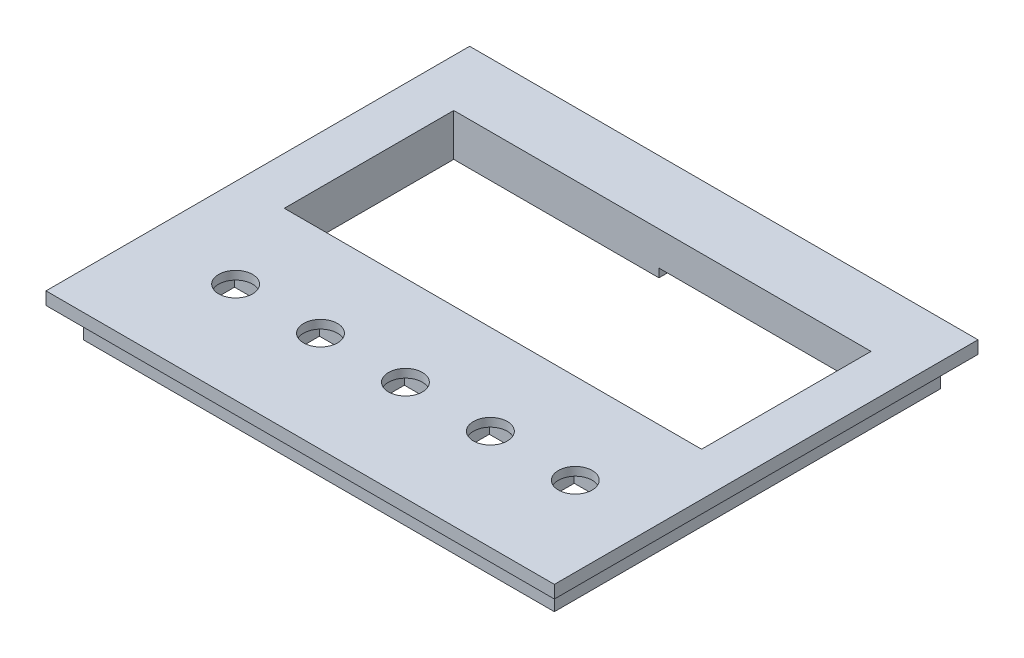
SolidWorks part; units mm, degrees
ref_plane "Front Plane" through (0, 0, 0) normal (0, 0, 1) x (1, 0, 0)
ref_plane "Top Plane" through (0, 0, 0) normal (0, 1, 0) x (1, 0, 0)
ref_plane "Right Plane" through (0, 0, 0) normal (1, 0, 0) x (0, 0, -1)
sketch "Sketch1" plane through (0, 0, 0) normal (0, 1, 0) x (1, 0, 0)
  line L1 (-59.6887, 52.0519) -> (60.3113, 52.0519)
  line L2 (-59.6887, 52.0519) -> (-59.6887, -47.9481)
  line L3 (-59.6887, -47.9481) -> (60.3113, -47.9481)
  line L4 (60.3113, 52.0519) -> (60.3113, -47.9481)
  dimension "D1" = 100
  dimension "D2" = 120
extrude "Boss-Extrude1" add sketch "Sketch1" along normal blind 10
sketch "Sketch2" plane through (0, 10, 0) normal (0, 1, 0) x (1, 0, 0)
  line L0 (60.3113, 52.0519) -> (-59.6887, 52.0519) construction
  line L1 (-48.4387, 37.0519) -> (50.0613, 37.0519)
  line L2 (-48.4387, 37.0519) -> (-48.4387, -2.9481)
  line L3 (-48.4387, -2.9481) -> (50.0613, -2.9481)
  line L4 (50.0613, 37.0519) -> (50.0613, -2.9481)
  line L5 (-59.6887, 52.0519) -> (-59.6887, -47.9481) construction
  dimension "D1" = 98.5
  dimension "D2" = 40
  dimension "D3" = 15
  dimension "D4" = 11.25
extrude "Cut-Extrude1" cut sketch "Sketch2" against normal blind 10
sketch "Sketch3" plane through (0, 0, 0) normal (0, -1, 0) x (1, 0, 0)
  line L0 (-59.6887, 47.9481) -> (60.3113, 47.9481) construction
  line L1 (-55.2887, 43.5481) -> (55.9113, 43.5481)
  line L2 (-55.2887, 43.5481) -> (-55.2887, -47.6519)
  line L3 (-55.2887, -47.6519) -> (55.9113, -47.6519)
  line L4 (55.9113, 43.5481) -> (55.9113, -47.6519)
  line L5 (-59.6887, -52.0519) -> (-59.6887, 47.9481) construction
  line L7 (60.3113, -52.0519) -> (-59.6887, -52.0519)
  line L8 (60.3113, -52.0519) -> (60.3113, 47.9481)
  line L9 (60.3113, 47.9481) -> (-59.6887, 47.9481)
  line L10 (-59.6887, -52.0519) -> (-59.6887, 47.9481)
  dimension "D1" = 4.4
  dimension "D2" = 4.4
  dimension "D3" = 4.4
  dimension "D4" = 4.4
extrude "Cut-Extrude3" cut sketch "Sketch3" against normal blind 7
sketch "Sketch4" plane through (0, 0, 0) normal (0, -1, 0) x (1, 0, 0)
  line L0 (-48.4387, 2.9481) -> (50.0613, 2.9481) construction
  line L1 (-48.1793, 39.9481) -> (-30.1793, 39.9481)
  line L2 (-48.1793, 39.9481) -> (-48.1793, 14.9481)
  line L3 (-48.1793, 14.9481) -> (-30.1793, 14.9481)
  line L4 (-30.1793, 39.9481) -> (-30.1793, 14.9481)
  line L5 (-28.1338, 39.9481) -> (-10.1338, 39.9481)
  line L6 (-28.1338, 39.9481) -> (-28.1338, 14.9481)
  line L7 (-28.1338, 14.9481) -> (-10.1338, 14.9481)
  line L8 (-10.1338, 39.9481) -> (-10.1338, 14.9481)
  line L9 (-8.0883, 39.9481) -> (9.9117, 39.9481)
  line L10 (-8.0883, 39.9481) -> (-8.0883, 14.9481)
  line L11 (-8.0883, 14.9481) -> (9.9117, 14.9481)
  line L12 (9.9117, 39.9481) -> (9.9117, 14.9481)
  line L13 (11.9573, 39.9481) -> (29.9573, 39.9481)
  line L14 (11.9573, 39.9481) -> (11.9573, 14.9481)
  line L15 (11.9573, 14.9481) -> (29.9573, 14.9481)
  line L16 (29.9573, 39.9481) -> (29.9573, 14.9481)
  line L17 (32.0028, 39.9481) -> (50.0028, 39.9481)
  line L18 (32.0028, 39.9481) -> (32.0028, 14.9481)
  line L19 (32.0028, 14.9481) -> (50.0028, 14.9481)
  line L20 (50.0028, 39.9481) -> (50.0028, 14.9481)
  line L21 (-48.1793, -19.4827) -> (-48.1793, 51.1477) construction
  line L23 (50.0028, -6.721) -> (50.0028, 58.8046) construction
  dimension "D1" = 18
  dimension "D2" = 25
  dimension "D3" = 12
  dimension "D5" = 0
  dimension "D6" = 0
  dimension "D4" = 5
extrude "Cut-Extrude4" cut sketch "Sketch4" against normal blind 8
sketch "Sketch5" plane through (0, 8, 0) normal (0, -1, 0) x (1, 0, 0)
  line L0 (50.0028, 39.9481) -> (32.0028, 39.9481) construction
  line L1 (32.0028, 14.9481) -> (35.0028, 14.9481)
  line L2 (32.0028, 14.9481) -> (32.0028, 39.9481)
  line L3 (32.0028, 39.9481) -> (35.0028, 39.9481)
  line L4 (35.0028, 14.9481) -> (35.0028, 39.9481)
  line L5 (11.9573, 14.9481) -> (14.9573, 14.9481)
  line L6 (11.9573, 14.9481) -> (11.9573, 39.9481)
  line L7 (11.9573, 39.9481) -> (14.9573, 39.9481)
  line L8 (14.9573, 14.9481) -> (14.9573, 39.9481)
  line L9 (-8.0883, 14.9481) -> (-5.0883, 14.9481)
  line L10 (-8.0883, 14.9481) -> (-8.0883, 39.9481)
  line L11 (-8.0883, 39.9481) -> (-5.0883, 39.9481)
  line L12 (-5.0883, 14.9481) -> (-5.0883, 39.9481)
  line L13 (-28.1338, 14.9481) -> (-25.1338, 14.9481)
  line L14 (-28.1338, 14.9481) -> (-28.1338, 39.9481)
  line L15 (-28.1338, 39.9481) -> (-25.1338, 39.9481)
  line L16 (-25.1338, 14.9481) -> (-25.1338, 39.9481)
  line L17 (-48.1793, 14.9481) -> (-45.1793, 14.9481)
  line L18 (-48.1793, 14.9481) -> (-48.1793, 39.9481)
  line L19 (-48.1793, 39.9481) -> (-45.1793, 39.9481)
  line L20 (-45.1793, 14.9481) -> (-45.1793, 39.9481)
  line L21 (-48.1793, 39.9481) -> (-48.1793, 14.9481) construction
  dimension "D1" = 3
  dimension "D3" = 0
  dimension "D2" = 5
extrude "Cut-Extrude6" cut sketch "Sketch5" against normal blind 1
sketch "Sketch6" plane through (0, 8, 0) normal (0, -1, 0) x (1, 0, 0)
  line L0 (35.0028, 14.9481) -> (50.0028, 14.9481) construction
  line L1 (50.0028, 14.9481) -> (50.0028, 39.9481) construction
  line L2 (-30.1793, 14.9481) -> (-30.1793, 39.9481) construction
  circle A0 centre (41.5028, 24.1981) radius 4
  circle A1 centre (21.4573, 24.1981) radius 4
  circle A2 centre (1.4117, 24.1981) radius 4
  circle A3 centre (-18.6338, 24.1981) radius 4
  circle A4 centre (-38.6793, 24.1981) radius 4
  dimension "D1" = 9.25
  dimension "D2" = 8.5
  dimension "D4" = 8.5
  dimension "D3" = 5
extrude "Cut-Extrude12" cut sketch "Sketch6" against normal through all
sketch "Sketch7" plane through (0, 0, 0) normal (0, -1, 0) x (1, 0, 0)
  line L0 (0, -42.9877) -> (0, -66.49) construction
  line L1 (50.0613, -37.0519) -> (-48.4387, -37.0519) construction
  line L2 (0, -37.0519) -> (45.0613, -37.0519)
  line L3 (0, -37.0519) -> (0, -42.0519)
  line L4 (0, -42.0519) -> (45.0613, -42.0519)
  line L6 (45.0613, -37.0519) -> (45.0613, -42.0519)
  line L7 (50.0613, 2.9481) -> (50.0613, -37.0519) construction
  dimension "D1" = 5
  dimension "D2" = 5
extrude "Cut-Extrude13" cut sketch "Sketch7" against normal blind 2
